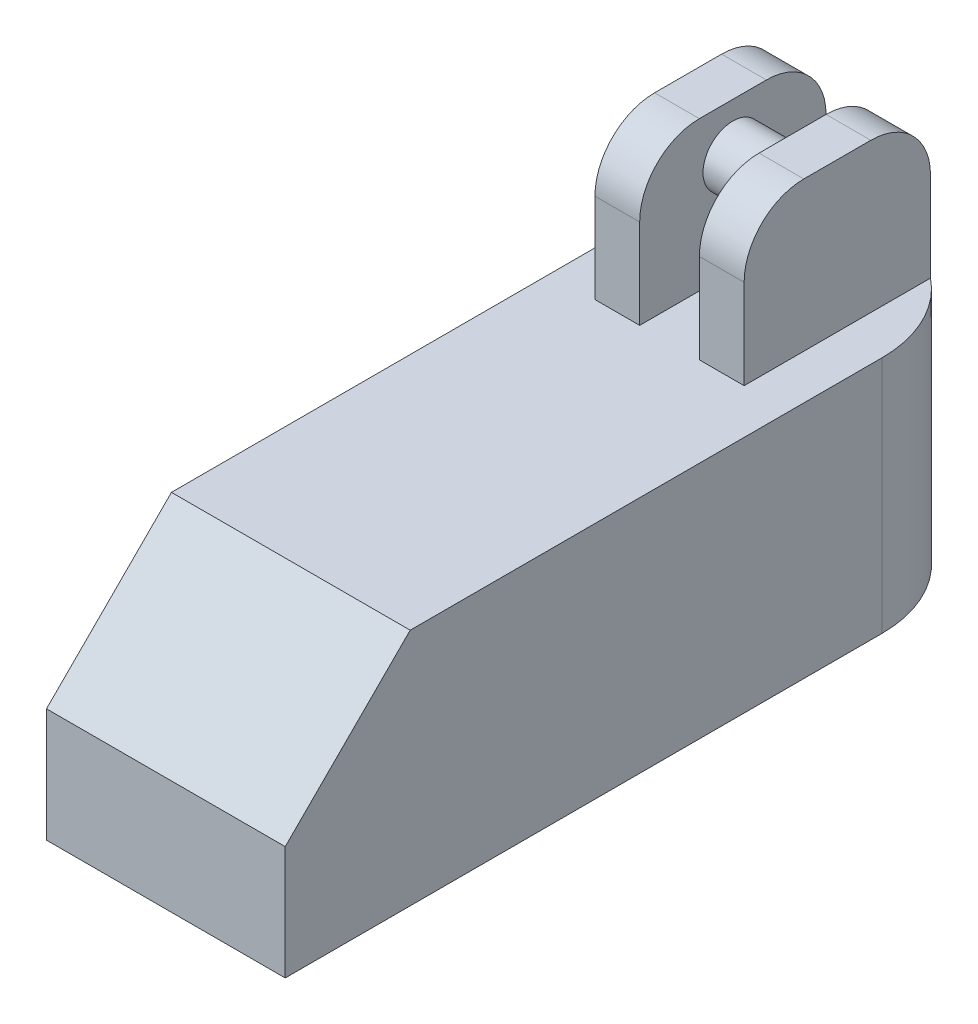
SolidWorks part; units mm, degrees
ref_plane "Front Plane" through (0, 0, 0) normal (0, 0, 1) x (1, 0, 0)
ref_plane "Top Plane" through (0, 0, 0) normal (0, 1, 0) x (1, 0, 0)
ref_plane "Right Plane" through (0, 0, 0) normal (1, 0, 0) x (0, 0, -1)
sketch "Sketch1" plane through (0, 0, 0) normal (0, 1, 0) x (1, 0, 0)
  circle A0 centre (0, 0) radius 50.8
  dimension "D1" = 101.6
extrude "Boss-Extrude1" add sketch "Sketch1" along normal blind 203.2
sketch "Sketch2" plane through (0, 203.2, 0) normal (0, 1, 0) x (1, 0, 0)
  line L1 (-31.75, -39.6557) -> (31.75, -39.6557)
  line L2 (-31.75, -39.6557) -> (-31.75, 39.6557)
  line L3 (-31.75, 39.6557) -> (31.75, 39.6557)
  line L4 (31.75, -39.6557) -> (31.75, 39.6557)
  line L5 (-31.75, -39.6557) -> (31.75, 39.6557) construction
  line L6 (-31.75, 39.6557) -> (31.75, -39.6557) construction
  circle A0 centre (0, 0) radius 50.8 construction
  point P0 (0, 0)
  dimension "D1" = 63.5
extrude "Boss-Extrude2" add sketch "Sketch2" along normal blind 63.5
sketch "Sketch3" plane through (0, 266.7, 0) normal (0, 1, 0) x (1, 0, 0)
  line L0 (31.75, 39.6557) -> (-31.75, 39.6557) construction
  line L1 (-12.7, -39.6557) -> (12.7, -39.6557)
  line L2 (-12.7, -39.6557) -> (-12.7, 39.6557)
  line L3 (-12.7, 39.6557) -> (12.7, 39.6557)
  line L4 (12.7, -39.6557) -> (12.7, 39.6557)
  line L5 (-12.7, -39.6557) -> (12.7, 39.6557) construction
  line L6 (-12.7, 39.6557) -> (12.7, -39.6557) construction
  point P0 (0, 0)
  dimension "D1" = 25.4
extrude "Cut-Extrude1" cut sketch "Sketch3" against normal blind 63.5
fillet "Fillet1" radius 25.4 4 edges at (-22.225, 266.7, -39.6557) (-22.225, 266.7, 39.6557) (22.225, 266.7, -39.6557) (22.225, 266.7, 39.6557)
sketch "Sketch4" plane through (0, 0, 0) normal (0, -1, 0) x (1, 0, 0)
  circle A0 centre (0, 0) radius 31.75
extrude "Cut-Extrude2" cut sketch "Sketch4" against normal blind 63.5
sketch "Sketch5" plane through (31.75, 0, 0) normal (1, 0, 0) x (0, 0, -1)
  circle A0 centre (0, 245.9935) radius 12.7
sketch "Sketch6" plane through (0, 0, 0) normal (0, 0, 1) x (1, 0, 0)
  line L0 (50.8, 0) -> (50.8, 203.2) construction
  line L1 (-50.8, 203.2) -> (50.8, 203.2)
  line L2 (-50.8, 203.2) -> (-50.8, 101.6)
  line L3 (-50.8, 101.6) -> (50.8, 101.6)
  line L4 (50.8, 203.2) -> (50.8, 101.6)
extrude "Boss-Extrude3" add sketch "Sketch6" along normal blind 254
sketch "Sketch7" plane through (0, 0, 254) normal (0, 0, 1) x (1, 0, 0)
  line L0 (55.88, 0) -> (-55.88, 0) construction
  line L1 (-50.8, 101.6) -> (55.2665, 101.6)
  line L2 (-50.8, 101.6) -> (-50.8, 0)
  line L3 (-50.8, 0) -> (55.2665, 0)
  line L4 (55.2665, 101.6) -> (55.2665, 0)
extrude "Cut-Extrude4" cut sketch "Sketch7" against normal through all
chamfer "Chamfer2" distance 53.18 1 edges at (0, 203.2, 254)
extrude "Boss-Extrude5" add sketch "Sketch5" against normal blind 53.34
sketch "Sketch11" plane through (0, 101.6, 0) normal (0, -1, 0) x (1, 0, 0)
  circle A0 centre (0, 127) radius 38.1
extrude "Cut-Extrude7" cut sketch "Sketch11" against normal blind 50.8
